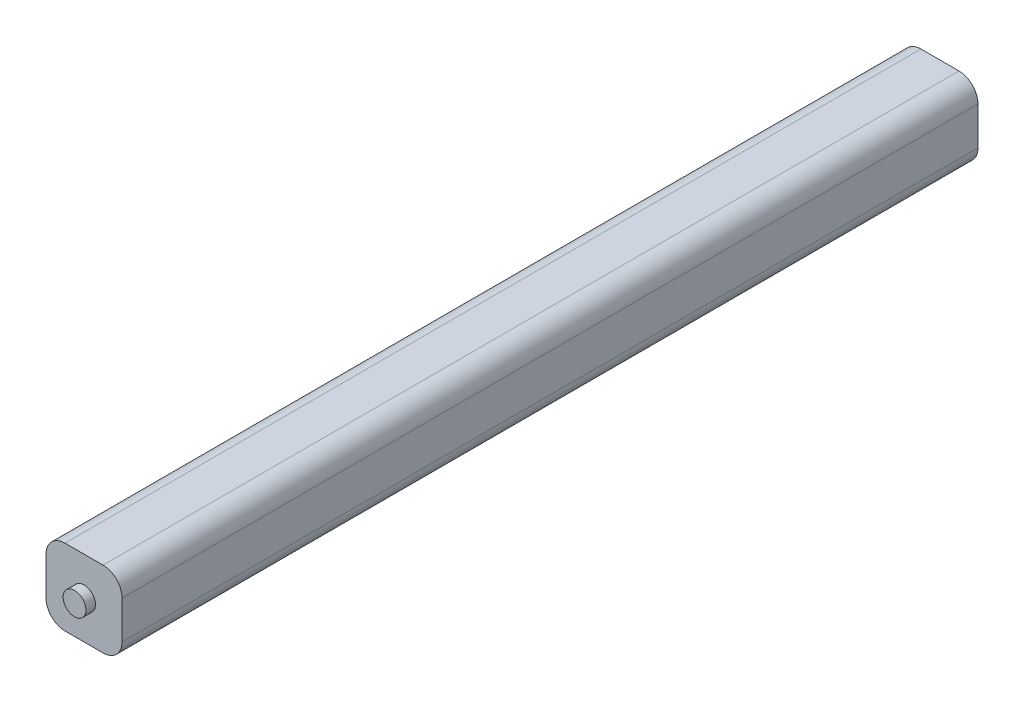
SolidWorks part; units mm, degrees
ref_plane "前视基准面" through (0, 0, 0) normal (0, 0, 1) x (1, 0, 0)
ref_plane "上视基准面" through (0, 0, 0) normal (0, 1, 0) x (1, 0, 0)
ref_plane "右视基准面" through (0, 0, 0) normal (1, 0, 0) x (0, 0, -1)
sketch "草图1" plane through (0, 0, 0) normal (0, 0, 1) x (1, 0, 0)
  circle A0 centre (0, 0) radius 6
  dimension "D1" = 12
extrude "凸台-拉伸1" add sketch "草图1" along normal mid plane 460
sketch "草图2" plane through (0, 0, 0) normal (0, 0, 1) x (1, 0, 0)
  line L1 (-20, 20) -> (20, 20)
  line L2 (-20, 20) -> (-20, -20)
  line L3 (-20, -20) -> (20, -20)
  line L4 (20, 20) -> (20, -20)
  line L5 (-20, 20) -> (20, -20) construction
  line L6 (-20, -20) -> (20, 20) construction
  point P0 (0, 0)
  dimension "D1" = 40
  dimension "D2" = 40
extrude "凸台-拉伸2" add sketch "草图2" along normal mid plane 450
fillet "圆角1" radius 10 4 edges at (20, -20, 0) (-20, -20, 0) (20, 20, 0) (-20, 20, 0)
